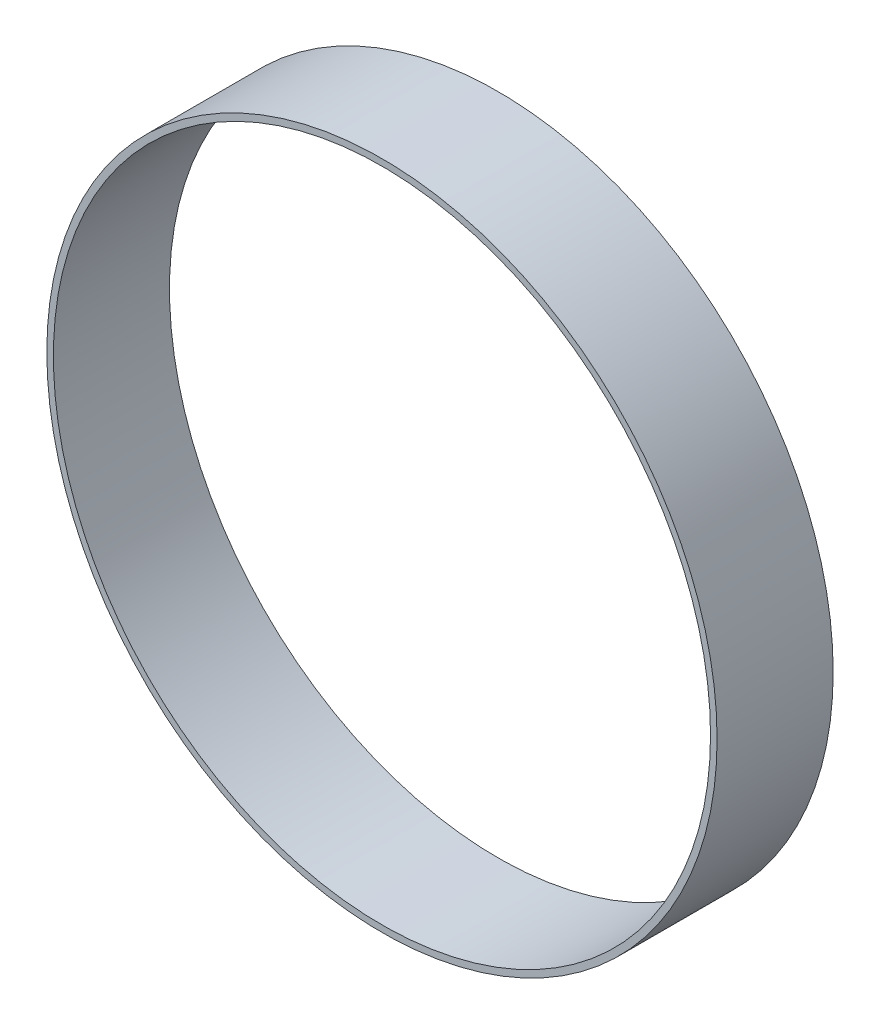
SolidWorks part; units mm, degrees
ref_plane "Front Plane" through (0, 0, 0) normal (0, 0, 1) x (1, 0, 0)
ref_plane "Top Plane" through (0, 0, 0) normal (0, 1, 0) x (1, 0, 0)
ref_plane "Right Plane" through (0, 0, 0) normal (1, 0, 0) x (0, 0, -1)
sketch "Sketch1" plane through (0, 0, 0) normal (0, 0, 1) x (1, 0, 0)
  arc A0 (-93.9534, 116.9306) -> (16.2473, 149.1175) centre (0, 0) ccw
  arc A1 (16.2473, 149.1175) -> (-93.9534, 116.9306) centre (0, 0) ccw
  dimension "D2" = 150
extrude "Extrude-Thin1" add sketch "Sketch1" along normal blind 53 thin
